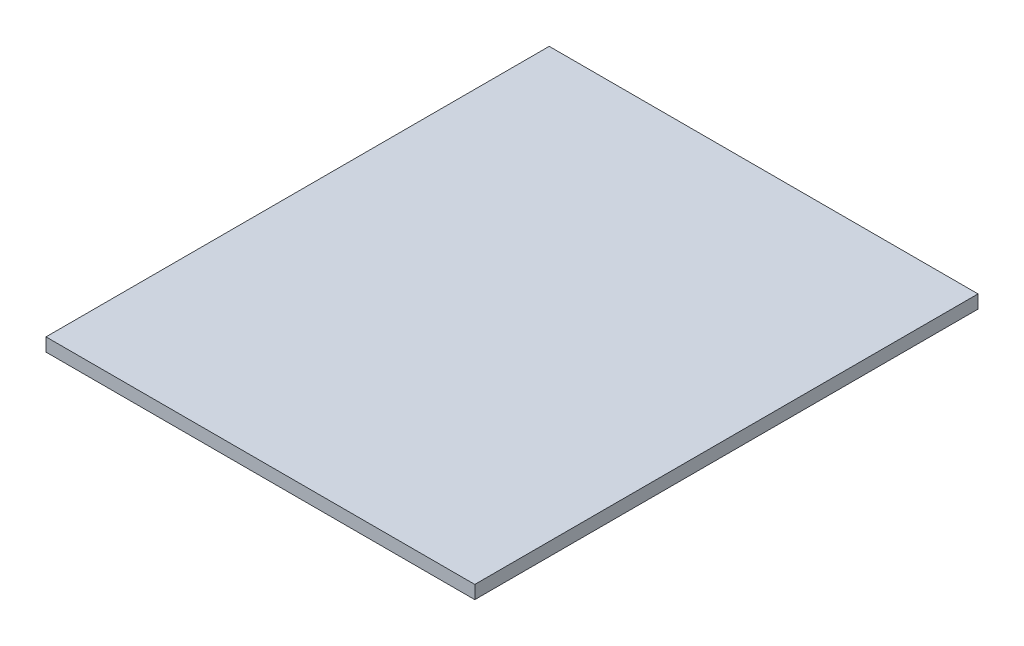
SolidWorks part; units mm, degrees
ref_plane "前视基准面" through (0, 0, 0) normal (0, 0, 1) x (1, 0, 0)
ref_plane "上视基准面" through (0, 0, 0) normal (0, 1, 0) x (1, 0, 0)
ref_plane "右视基准面" through (0, 0, 0) normal (1, 0, 0) x (0, 0, -1)
other "Configuration Table"
sketch "草图1" plane through (0, 0, 0) normal (0, 1, 0) x (1, 0, 0)
  line L0 (0, 0) -> (0, 37.32)
  line L1 (0, 37.32) -> (31.8, 37.32)
  line L2 (31.8, 37.32) -> (31.8, 0)
  line L3 (31.8, 0) -> (0, 0)
extrude "凸台-拉伸1" add sketch "草图1" along normal blind 0.98
sketch "草图2" plane through (0, 0.98, 0) normal (0, 1, 0) x (1, 0, 0)
  text T0 "1.54'\r\n200x200"
